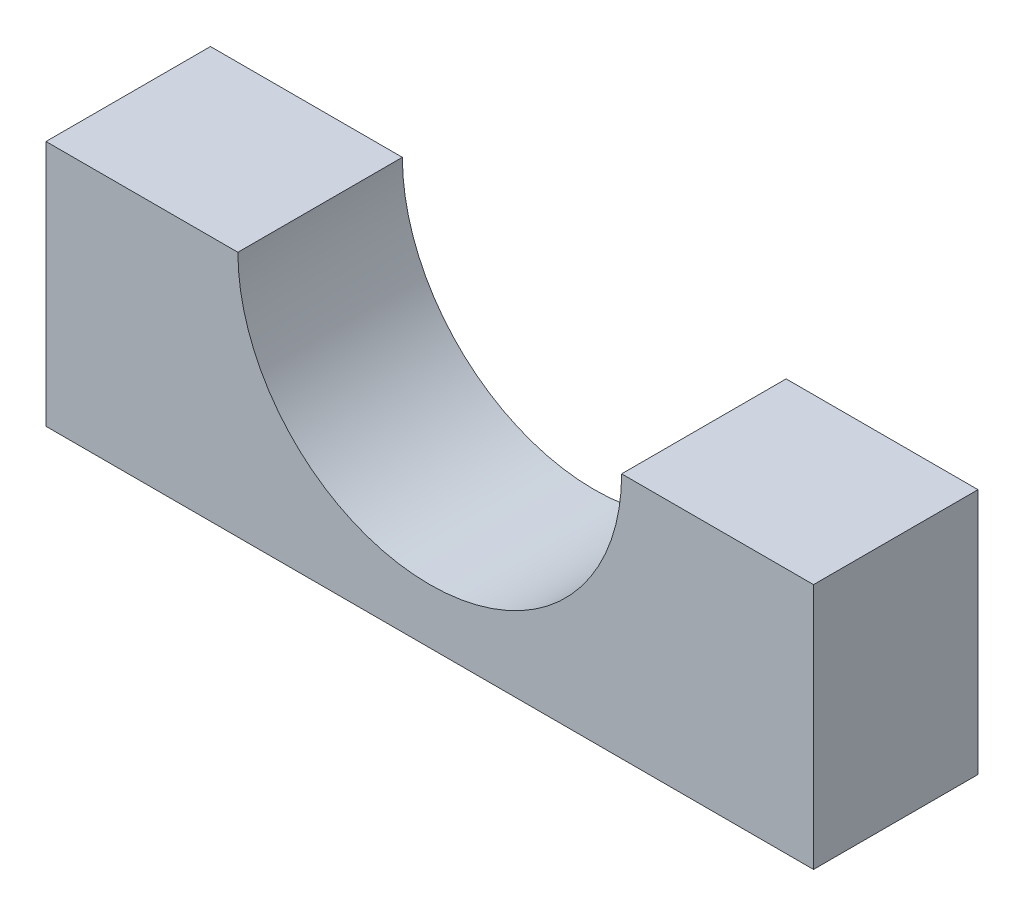
SolidWorks part; units mm, degrees
ref_plane "Front Plane" through (0, 0, 0) normal (0, 0, 1) x (1, 0, 0)
ref_plane "Top Plane" through (0, 0, 0) normal (0, 1, 0) x (1, 0, 0)
ref_plane "Right Plane" through (0, 0, 0) normal (1, 0, 0) x (0, 0, -1)
sketch "profiil" plane through (0, 0, 0) normal (0, 0, 1) x (1, 0, 0)
  line L3 (35, 22.5) -> (17.5, 22.5)
  line L11 (35, 0) -> (-35, 0)
  line L12 (0, 0) -> (0, 28.2018) construction
  line L13 (-35, 0) -> (-35, 22.5)
  line L14 (-35, 22.5) -> (-17.5, 22.5)
  line L15 (35, 0) -> (35, 22.5)
  arc A2 (-17.5, 22.5) -> (17.5, 22.5) centre (0, 22.5) ccw
  dimension "D3" = 17.5
  dimension "D2" = 22.5
  dimension "D5" = 35
extrude "Boss-Extrude1" add sketch "profiil" along normal blind 15 contours A2 L3 L15 L11 L13 L14
sketch "Sketch5" plane through (0, 0, 0) normal (0, 1, 0) x (1, 0, 0)
  line L0 (-35, -15) -> (-17.5, -15) construction
  line L1 (0, 0) -> (0, -25.4531) construction
  circle A0 centre (-25, -7.5) radius 5
  circle A1 centre (25, -7.5) radius 5
  dimension "D1" = 10
  dimension "D2" = 25
  dimension "D3" = 7.5
extrude "Boss-Extrude4" add sketch "Sketch5" along normal through all
